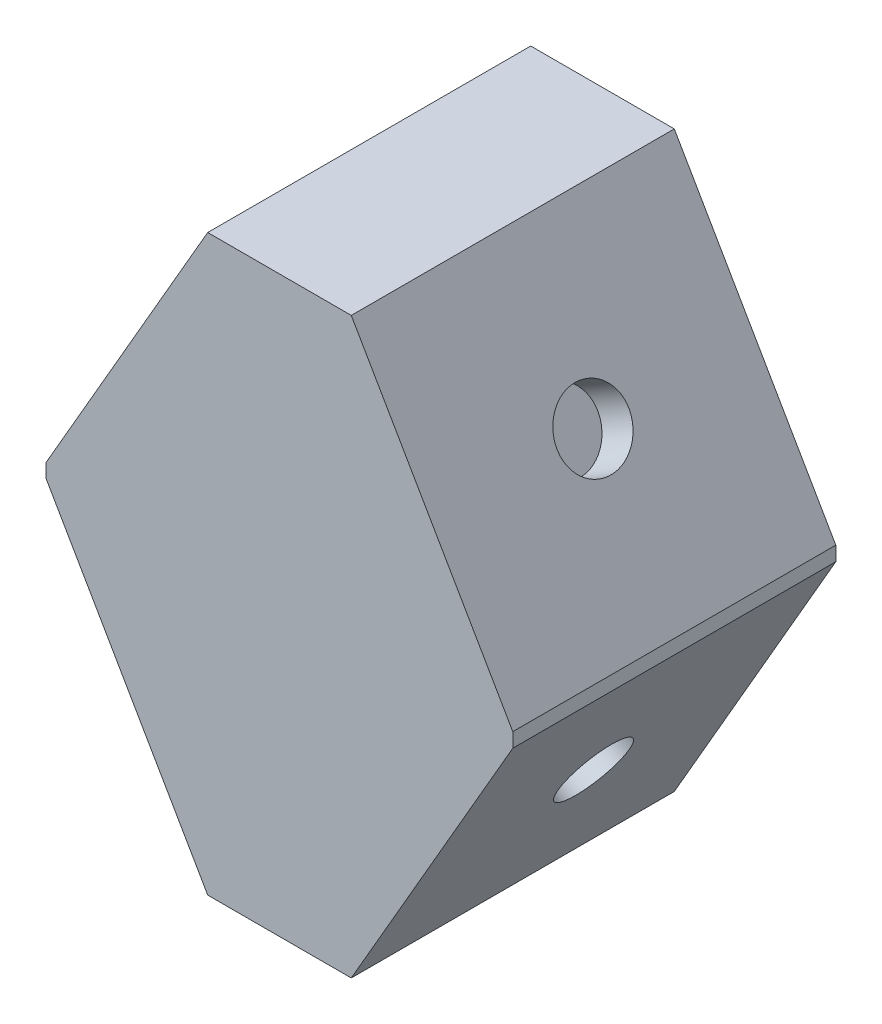
SolidWorks part; units mm, degrees
ref_plane "Front Plane" through (0, 0, 0) normal (0, 0, 1) x (1, 0, 0)
ref_plane "Top Plane" through (0, 0, 0) normal (0, 1, 0) x (1, 0, 0)
ref_plane "Right Plane" through (0, 0, 0) normal (1, 0, 0) x (0, 0, -1)
sketch "Sketch2" plane through (0, 0, 0) normal (0, 0, 1) x (1, 0, 0)
  line L0 (0, 64.2055) -> (0, -71.0162) construction
  line L1 (-77.7029, 0) -> (85.8757, 0) construction
  line L2 (-10, 39.9711) -> (10, 39.9711)
  line L3 (-10, 39.9711) -> (-32.5, 1)
  line L4 (-32.5, 1) -> (-32.5, -1)
  line L5 (32.5, 1) -> (32.5, -1)
  line L6 (10, 39.9711) -> (32.5, 1)
  line L7 (10, -39.9711) -> (32.5, -1)
  line L8 (-10, -39.9711) -> (10, -39.9711)
  line L9 (-10, -39.9711) -> (-32.5, -1)
  point P11 (0, 0)
  point P13 (32.5, 0)
  point P16 (-32.5, 0)
  dimension "D2" = 10
  dimension "D3" = 45
  dimension "D4" = 120
  dimension "D5" = 1
extrude "Boss-Extrude1" add sketch "Sketch2" along normal blind 45
sketch "Sketch3" plane through (24.808, 14.3229, 0) normal (0.866, 0.5, 0) x (0, 0, -1)
  line L0 (-22.5, 29.616) -> (-22.5, -15.384) construction
  line L1 (-45, 29.616) -> (0, 29.616) construction
  line L2 (-45, -15.384) -> (0, -15.384) construction
  line L3 (-45, 7.116) -> (0, 7.116) construction
  line L4 (-45, -15.384) -> (-45, 29.616) construction
  line L5 (0, -15.384) -> (0, 29.616) construction
  circle A0 centre (-22.5, 7.2819) radius 5
extrude "Cut-Extrude1" cut sketch "Sketch3" against normal blind 5
sketch "Sketch4" plane through (-24.808, 14.3229, 0) normal (-0.866, 0.5, 0) x (0, 0, 1)
  line L0 (22.5, 29.616) -> (22.5, -15.384) construction
  line L1 (45, 29.616) -> (0, 29.616) construction
  line L2 (45, -15.384) -> (0, -15.384) construction
  line L3 (0, 7.116) -> (45, 7.116) construction
  line L4 (0, 29.616) -> (0, -15.384) construction
  line L5 (45, 29.616) -> (45, -15.384) construction
  circle A0 centre (22.5, 7.116) radius 5
  point P14 (22.5, 7.116)
extrude "Cut-Extrude2" cut sketch "Sketch4" against normal blind 5
sketch "Sketch5" plane through (-24.808, -14.3229, 0) normal (-0.866, -0.5, 0) x (0, 0, 1)
  line L0 (22.5, 15.384) -> (22.5, -29.616) construction
  line L1 (45, 15.384) -> (0, 15.384) construction
  line L2 (45, -29.616) -> (0, -29.616) construction
  line L3 (0, -7.116) -> (45, -7.116) construction
  line L4 (0, 15.384) -> (0, -29.616) construction
  line L5 (45, 15.384) -> (45, -29.616) construction
  circle A0 centre (22.5, -7.116) radius 5
extrude "Cut-Extrude3" cut sketch "Sketch5" against normal blind 5
sketch "Sketch6" plane through (24.808, -14.3229, 0) normal (0.866, -0.5, 0) x (0, 0, -1)
  line L0 (-22.5, -29.616) -> (-22.5, 15.384) construction
  line L1 (-45, -29.616) -> (0, -29.616) construction
  line L2 (-45, 15.384) -> (0, 15.384) construction
  line L3 (0, -7.116) -> (-45, -7.116) construction
  line L4 (0, -29.616) -> (0, 15.384) construction
  line L5 (-45, -29.616) -> (-45, 15.384) construction
  circle A0 centre (-22.5, -7.116) radius 5
extrude "Cut-Extrude4" cut sketch "Sketch6" against normal blind 5
